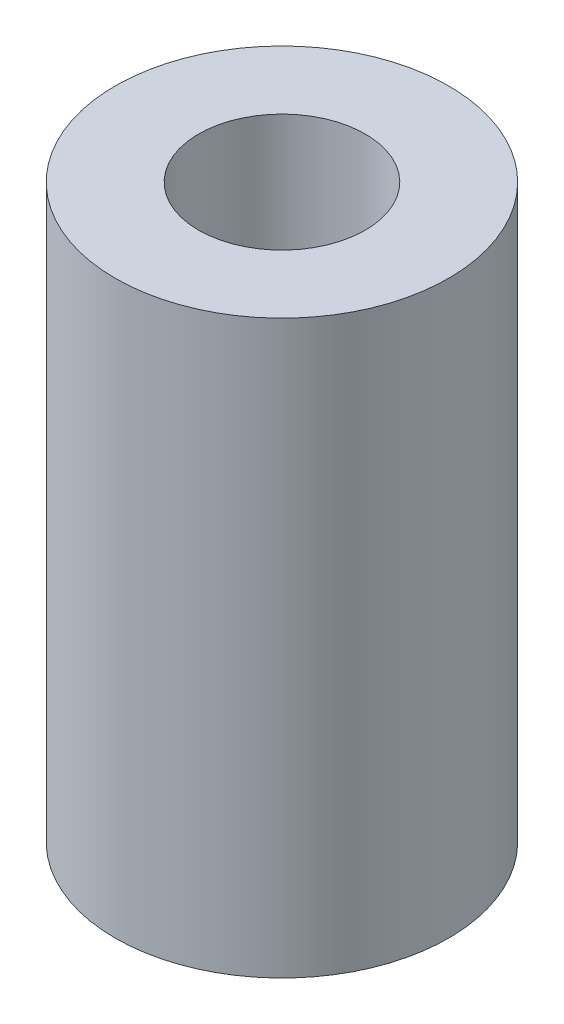
SolidWorks part; units mm, degrees
material "6061 Alloy"
ref_plane "Front Plane" through (0, 0, 0) normal (0, 0, 1) x (1, 0, 0)
ref_plane "Top Plane" through (0, 0, 0) normal (0, 1, 0) x (1, 0, 0)
ref_plane "Right Plane" through (0, 0, 0) normal (1, 0, 0) x (0, 0, -1)
sketch "Sketch1" plane through (0, 0, 0) normal (0, 1, 0) x (1, 0, 0)
  circle A0 centre (0, 0) radius 1.75
  circle A1 centre (0, 0) radius 3.5
  dimension "D1" = 3.5
  dimension "D2" = 7
extrude "Boss-Extrude1" add sketch "Sketch1" along normal blind 12
